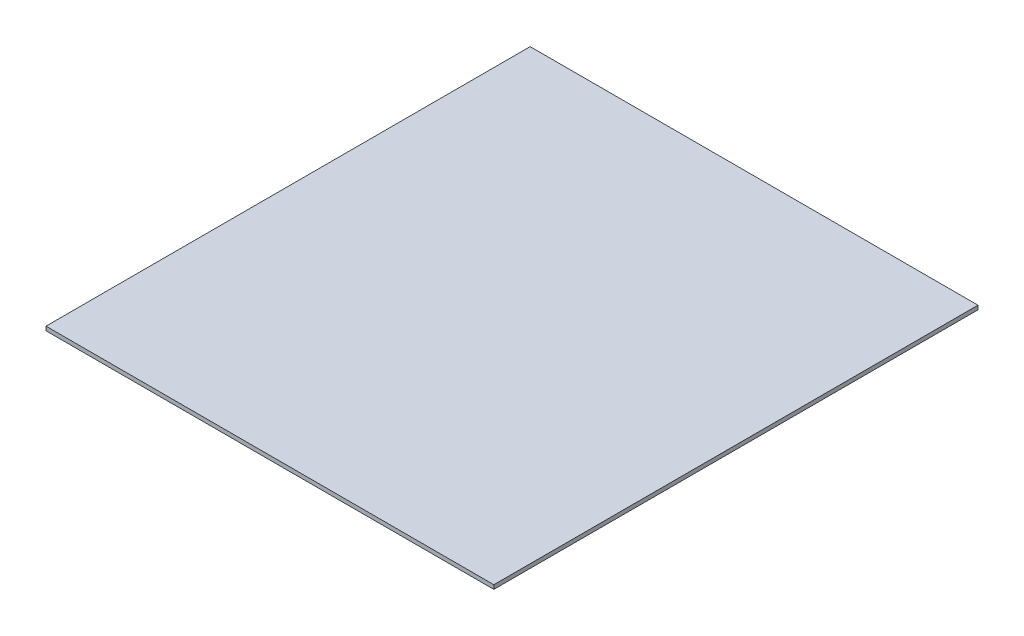
SolidWorks part; units mm, degrees
ref_plane "Front Plane" through (0, 0, 0) normal (0, 0, 1) x (1, 0, 0)
ref_plane "Top Plane" through (0, 0, 0) normal (0, 1, 0) x (1, 0, 0)
ref_plane "Right Plane" through (0, 0, 0) normal (1, 0, 0) x (0, 0, -1)
sketch "Sketch2" plane through (0, 0, 0) normal (0, 1, 0) x (1, 0, 0)
  line L1 (-555, 600) -> (555, 600)
  line L2 (-555, 600) -> (-555, -600)
  line L3 (-555, -600) -> (555, -600)
  line L4 (555, 600) -> (555, -600)
  line L5 (-555, 600) -> (555, -600) construction
  line L6 (-555, -600) -> (555, 600) construction
  point P0 (0, 0)
  dimension "D1" = 1110
  dimension "D2" = 1200
extrude "Boss-Extrude1" add sketch "Sketch2" along normal blind 10
